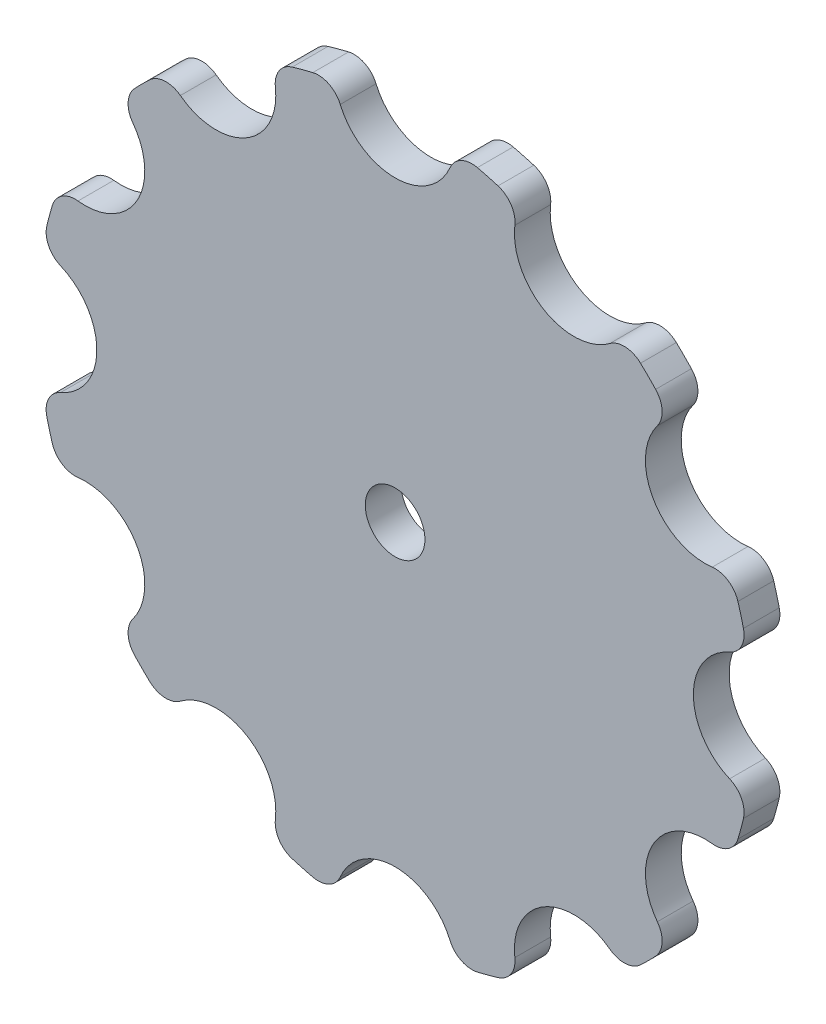
SolidWorks part; units mm, degrees
ref_plane "Front Plane" through (0, 0, 0) normal (0, 0, 1) x (1, 0, 0)
ref_plane "Top Plane" through (0, 0, 0) normal (0, 1, 0) x (1, 0, 0)
ref_plane "Right Plane" through (0, 0, 0) normal (1, 0, 0) x (0, 0, -1)
sketch "Sketch1" plane through (0, 0, 0) normal (0, 0, 1) x (1, 0, 0)
  line L0 (0, 25) -> (0, 30) construction
  circle A0 centre (0, 0) radius 30
  circle A1 centre (0, 0) radius 25 construction
  circle A2 centre (0, 30) radius 5
  circle A3 centre (15, 25.9808) radius 5
  circle A4 centre (25.9808, 15) radius 5
  circle A5 centre (30, 0) radius 5
  circle A6 centre (25.9808, -15) radius 5
  circle A7 centre (15, -25.9808) radius 5
  circle A8 centre (0, -30) radius 5
  circle A9 centre (-15, -25.9808) radius 5
  circle A10 centre (-25.9808, -15) radius 5
  circle A11 centre (-30, 0) radius 5
  circle A12 centre (-25.9808, 15) radius 5
  circle A13 centre (-15, 25.9808) radius 5
  point P31 (0, 0)
  dimension "D1" = 60
  dimension "D2" = 50
  dimension "D3" = 12
extrude "Boss-Extrude1" add sketch "Sketch1" along normal blind 3 contours A13 A0 A12 A11 A10 A9 A8 A7 A6 A5 A4 A3 A2
fillet "Fillet1" radius 2 4 edges at (-23.1286, 19.1067, 1.5) (-19.1067, 23.1286, 1.5) (-10.4766, 28.1112, 1.5) (-4.9826, 29.5833, 1.5)
fillet "Fillet2" radius 2 20 edges at (-28.1112, 10.4766, 1.5) (-29.5833, -4.9826, 1.5) (-29.5833, 4.9826, 1.5) (-23.1286, -19.1067, 1.5) (-28.1112, -10.4766, 1.5) (-10.4766, -28.1112, 1.5) (-19.1067, -23.1286, 1.5) (4.9826, -29.5833, 1.5) (-4.9826, -29.5833, 1.5) (19.1067, -23.1286, 1.5) (10.4766, -28.1112, 1.5) (28.1112, -10.4766, 1.5) (23.1286, -19.1067, 1.5) (29.5833, 4.9826, 1.5) (29.5833, -4.9826, 1.5) (23.1286, 19.1067, 1.5) (28.1112, 10.4766, 1.5) (10.4766, 28.1112, 1.5) (19.1067, 23.1286, 1.5) (4.9826, 29.5833, 1.5)
sketch "Sketch2" plane through (0, 0, 0) normal (0, 0, -1) x (-1, 0, 0)
  circle A0 centre (0, 0) radius 2.5
  dimension "D1" = 5
extrude "Cut-Extrude1" cut sketch "Sketch2" against normal blind 10
